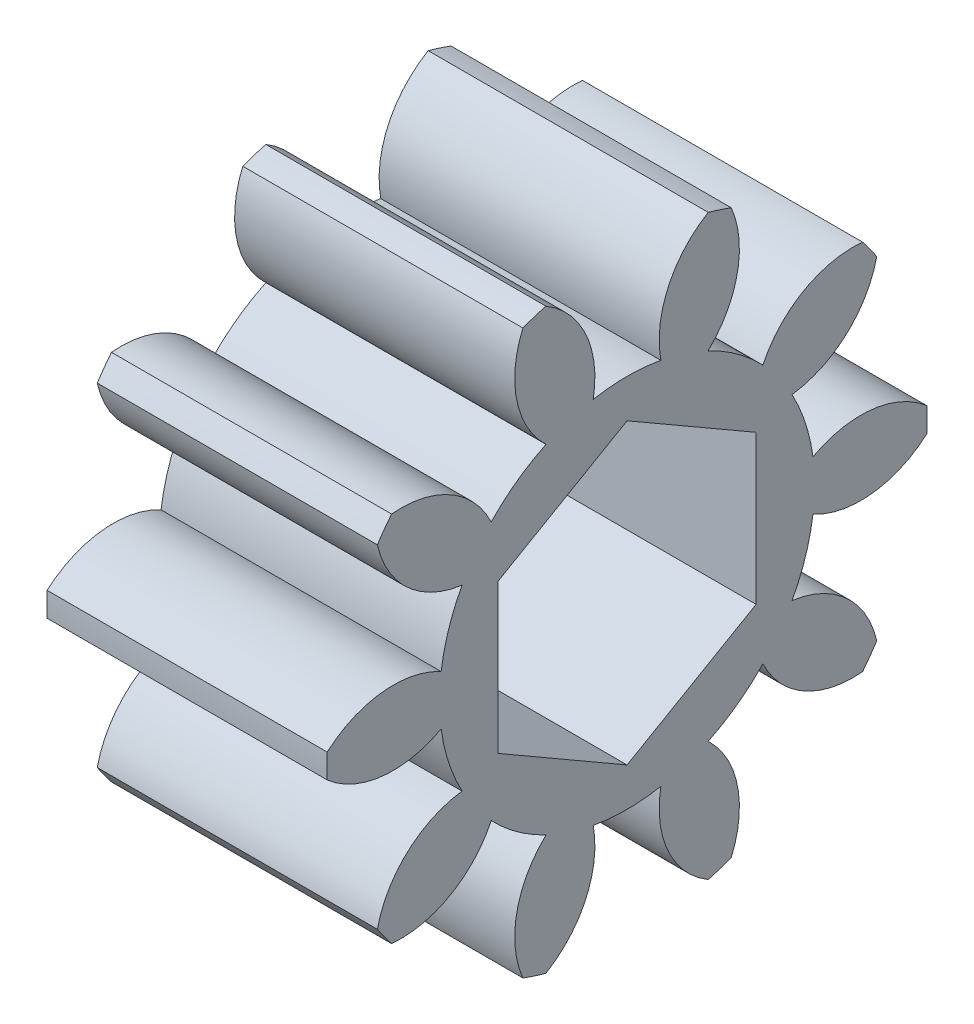
SolidWorks part; units mm, degrees
ref_plane "Plane1" through (0, 0, 0) normal (0, 0, 1) x (1, 0, 0)
ref_plane "Plane2" through (0, 0, 0) normal (0, 1, 0) x (1, 0, 0)
ref_plane "Plane3" through (0, 0, 0) normal (1, 0, 0) x (0, 0, -1)
other "Configuration Table"
sketch "HoldingSke" plane through (0, 0, 0) normal (0, 1, 0) x (1, 0, 0)
  line L0 (0, 0) -> (0.3939, -0.0695)
  line L1 (-15, 0) -> (100, 0) construction
  line L2 (0, 0) -> (-2.1039, 2.3779)
  line L3 (0, 0) -> (-11.863, 4.5341)
  line L4 (0, 0) -> (8.5048, 1.4996)
  line L5 (0, 0) -> (-46.8476, -17.4728)
  line L6 (0, 0) -> (-11.6055, -7.8303)
  line L7 (-2.1039, 2.3779) -> (8.6586, 51.2059)
  line L8 (-76.2, 54.61) -> (-74.4, 54.61)
  line L9 (-67.7845, 28.3722) -> (-49.3413, 33.142)
  line L10 (-76.2, 71.12) -> (104.1128, 71.12)
  line L11 (0, 0) -> (-14, 0)
  line L12 (-76.2, 101.6) -> (-76.113, 101.6)
  line L13 (24.9733, 27.94) -> (52.9518, 28.4284)
  line L14 (24.9733, 27.94) -> (24.9743, 27.94)
  line L15 (24.9733, 27.94) -> (100.4006, 29.5858)
  line L16 (-63.627, -2.5) -> (-12.827, -2.5)
  circle A0 centre (0, 0) radius 5
  circle A1 centre (0, 0) radius 9.374
  circle A2 centre (0, 0) radius 37.5
  circle A3 centre (0, 0) radius 5
  dimension "MHD" = 18.748
  dimension "Hub_dia" = 75
  dimension "Bore" = 10
  dimension "MBD" = 10
  dimension "Num_teeth" = 10
  dimension "Pitch" = 0.4
  dimension "Overall_len" = 50
  dimension "Show_teeth" = 10
  dimension "Thickness" = 14
  dimension "OAL" = 50.0001
  dimension "T_dim" = 1.8
  dimension "Ap" = 14.5
  dimension "H" = 19.05
  dimension "Pitch_radius" = 180.3128
  dimension "Width" = 14
  dimension "Backlash" = 0.087
  dimension "Addendum_fac" = 1
  dimension "Dedendum_fac" = 1.25
  dimension "Clearance_fac" = 0.25
  dimension "Dedendum_add" = 0.001
  dimension "Module" = 2.5
sketch "BasProSke" plane through (0, 0, 0) normal (0, 1, 0) x (1, 0, 0)
  line L0 (-10, 0) -> (60, 0) construction
  line L1 (0, 0) -> (0, 15)
  line L2 (0, 0) -> (14, 0)
  line L3 (14, 0) -> (14, 15)
  line L4 (14, 15) -> (0, 15)
  dimension "Thickness" = 14
  dimension "Diameter" = 30
revolve "Base-Revolve" add sketch "BasProSke" angle 360 about L0
sketch "TooCutSke" plane through (0, 0, 0) normal (1, 0, 0) x (0, 0, -1)
  line L1 (0, 0) -> (0, 107) construction
  line L2 (0, 0) -> (-2.1074, 12.3211) construction
  line L3 (0, 0) -> (-7.6446, 23.5277) construction
  line L4 (-2.1074, 12.3211) -> (-3.8223, 11.7639) construction
  arc A0 (1.6916, 9.2201) -> (-1.6916, 9.2201) centre (0, 0) ccw
  arc A1 (4.0875, 14.4587) -> (-4.0875, 14.4587) centre (0, 0) ccw
  circle A2 centre (0, 0) radius 12.5 construction
  circle A3 centre (0, 0) radius 12.1018 construction
  arc A4 (-1.6916, 9.2201) -> (-4.0875, 14.4587) centre (-6.6064, 10.1395) ccw
  arc A5 (4.0875, 14.4587) -> (1.6916, 9.2201) centre (6.6064, 10.1395) ccw
  dimension "Root_dia" = 18.748
  dimension "Overcut_dia" = 30.0508
  dimension "Pitch_dia" = 25
  dimension "Base_dia" = 24.2037
  dimension "Flank_rad" = 5
  dimension "Half_ang" = 18
  dimension "Half_CT" = 1.8032
extrude "ToothCut" cut sketch "TooCutSke" along normal through all
fillet "Breaks" [suppressed] radius 0.05
fillet "RootFillets" [suppressed] radius 0.626
pattern_circular "TeethCuts" count 10 every 36 about axis through (-10, 0, 0) along (1, 0, 0) of "ToothCut", "RootFillets", "Breaks"
sketch "HubNeaOneSke" plane through (0, 0, 0) normal (-1, 0, 0) x (0, 0, 1)
  circle A0 centre (0, 0) radius 9.374
  dimension "Diameter" = 18.748
extrude "HubNearOne" [suppressed] add sketch "HubNeaOneSke" along normal blind 36.0001
sketch "HubNeaBotSke" plane through (0, 0, 0) normal (-1, 0, 0) x (0, 0, 1)
  circle A0 centre (0, 0) radius 9.374
  dimension "Diameter" = 18.748
extrude "HubNearBoth" [suppressed] add sketch "HubNeaBotSke" along normal blind 18
ref_plane "FarPln" through (14, 0, 0) normal (1, 0, 0) x (0, 0, -1)
sketch "HubFarSke" plane through (14, 0, 0) normal (1, 0, 0) x (0, 0, -1)
  circle A0 centre (0, 0) radius 9.374
  dimension "Diameter" = 18.748
extrude "HubFar" [suppressed] add sketch "HubFarSke" along normal blind 18
sketch "BorSke" plane through (0, 0, 0) normal (1, 0, 0) x (0, 0, -1)
  circle A0 centre (0, 0) radius 5
  dimension "Diameter" = 10
extrude "Bore" cut sketch "BorSke" along normal mid plane 100.0001
sketch "KeySke" plane through (0, 0, 0) normal (1, 0, 0) x (0, 0, -1)
  line L0 (-2, 0) -> (-2, 6.8)
  line L1 (-2, 6.8) -> (2, 6.8)
  line L2 (2, 6.8) -> (2, 0)
  line L3 (0, 0) -> (0, 34) construction
  line L4 (-2, 0) -> (2, 0)
  dimension "Offset" = 6.8
  dimension "Width" = 4
extrude "Keyway" [suppressed] cut sketch "KeySke" along normal mid plane 100.0001
pattern_circular "Keyway2" [suppressed] count 2 every 90 about axis through (-10, 0, 0) along (1, 0, 0)
sketch "Sketch1" plane through (14, 0, 0) normal (1, 0, 0) x (0, 0, -1)
  line L1 (0, -7.4478) -> (6.45, -3.7239)
  line L2 (6.45, -3.7239) -> (6.45, 3.7239)
  line L3 (6.45, 3.7239) -> (0, 7.4478)
  line L4 (0, 7.4478) -> (-6.45, 3.7239)
  line L5 (-6.45, 3.7239) -> (-6.45, -3.7239)
  line L6 (-6.45, -3.7239) -> (0, -7.4478)
  circle A0 centre (0, 0) radius 6.45 construction
extrude "Cut-Extrude1" cut sketch "Sketch1" against normal through all
equation "' \"Module@HoldingSke\" = 6.35"
equation "' \"Num_teeth@HoldingSke\" = 12"
equation "' \"Ap@HoldingSke\" =  20"
equation "' \"Ap@HoldingSke\" = 20"
equation "' \"Width@HoldingSke\" = 0.5 * 25.4"
equation "' \"Hub_dia@HoldingSke\"= 1 * 25.4"
equation "' \"Hub_dia@HoldingSke\" = 1 * 25.4"
equation "' \"Overall_len@HoldingSke\" = 1.0 * 25.4"
equation "' \"Bore@HoldingSke\" = 0.75 * 25.4"
equation "' \"T_dim@HoldingSke\" = 0.1 * 25.4"
equation "' \"Width@KeySke\" = 0.25 * 25.4"
equation "' \"Show_teeth@HoldingSke\" = 13"
equation "' \"Backlash@HoldingSke\" = 0.009 * 25.4"
equation "' \"Addendum_fac@HoldingSke\" = 1.0"
equation "' \"Dedendum_fac@HoldingSke\" = 1.25"
equation "' \"Dedendum_add@HoldingSke\" = 0.00005 * 25.4"
equation "' \"Clearance_fac@HoldingSke\" = 0.25"
equation "\"Pitch@HoldingSke\" = 1 / \"Module@HoldingSke\""
equation "\"Overcut_dia@TooCutSke\" = (\"Num_teeth@HoldingSke\" + 2 * \"Addendum_fac@HoldingSke\") / \"Pitch@HoldingSke\" + 0.002 * 25.4"
equation "\"Pitch_dia@TooCutSke\" = \"Num_teeth@HoldingSke\" / \"Pitch@HoldingSke\""
equation "\"Base_dia@TooCutSke\" = \"Num_teeth@HoldingSke\" / \"Pitch@HoldingSke\" * cos((\"Ap@HoldingSke\"  * 3.14159265 / 180))"
equation "\"Root_dia@TooCutSke\" = (\"Num_teeth@HoldingSke\" + 2) / \"Pitch@HoldingSke\" - 2 * (\"Addendum_fac@HoldingSke\" + \"Dedendum_fac@HoldingSke\") / \"Pitch@HoldingSke\" - \"Dedendum_add@HoldingSke\" * 2"
equation "\"Half_ang@TooCutSke\" = 180 / \"Num_teeth@HoldingSke\""
equation "\"Half_CT@TooCutSke\" = \"Num_teeth@HoldingSke\" / \"Pitch@HoldingSke\" * sin((3.14159265 / 2 / \"Num_teeth@HoldingSke\")) / 2 - 7 * \"Backlash@HoldingSke\" / 4"
equation "\"Flank_rad@TooCutSke\" = \"Num_teeth@HoldingSke\" / \"Pitch@HoldingSke\" / 5"
equation "\"Radius@RootFillets\" = \"Clearance_fac@HoldingSke\" / \"Pitch@HoldingSke\" + \"Dedendum_add@HoldingSke\""
equation "\"Break_rad@Breaks\" = 0.02 / \"Pitch@HoldingSke\""
equation "\"Thickness@HoldingSke\" = \"Width@HoldingSke\""
equation "\"OAL@HoldingSke\" = \"Thickness@HoldingSke\""
equation "\"MHD@HoldingSke\" = (\"Num_teeth@HoldingSke\" + 2) / \"Pitch@HoldingSke\" - 2 * (\"Addendum_fac@HoldingSke\" + \"Dedendum_fac@HoldingSke\")  / \"Pitch@HoldingSke\" - \"Dedendum_add@HoldingSke\" * 2"
equation "\"MBD@HoldingSke\" = (\"Num_teeth@HoldingSke\" + 2) / \"Pitch@HoldingSke\" - 2 * (\"Addendum_fac@HoldingSke\" + \"Dedendum_fac@HoldingSke\")  / \"Pitch@HoldingSke\" - \"Dedendum_add@HoldingSke\" * 2 - 0.002 * 25.4"
equation "\"MHD@HoldingSke\" = ((sgn( \"MHD@HoldingSke\" - \"Hub_dia@HoldingSke\" )-1)*( \"MHD@HoldingSke\" - \"Hub_dia@HoldingSke\" ))/-2+ \"Hub_dia@HoldingSke\""
equation "\"MBD@HoldingSke\" = ((sgn( \"MBD@HoldingSke\" - \"Bore@HoldingSke\" )-1)*( \"MBD@HoldingSke\" - \"Bore@HoldingSke\" ))/-2+ \"Bore@HoldingSke\""
equation "\"OAL@HoldingSke\" = ((sgn( \"OAL@HoldingSke\" - \"Overall_len@HoldingSke\" )+1)*( \"OAL@HoldingSke\" - \"Overall_len@HoldingSke\" ))/2 + \"Overall_len@HoldingSke\" + 0.000002 * 25.4"
equation "\"Num_teeth@TeethCuts\" = int( \"Show_teeth@HoldingSke\" ) + 1"
equation "\"Num_teeth@TeethCuts\" = ((sgn( \"Num_teeth@TeethCuts\" - \"Num_teeth@HoldingSke\" )-1)*( \"Num_teeth@TeethCuts\" - \"Num_teeth@HoldingSke\" ))/-2+ \"Num_teeth@HoldingSke\""
equation "\"Num_teeth@TeethCuts\" = ((sgn( \"Num_teeth@TeethCuts\" - 2.0)+1)*( \"Num_teeth@TeethCuts\" - 2.0))/2 +2.0"
equation "\"Angle@TeethCuts\" = 360.0 / \"Num_teeth@HoldingSke\""
equation "\"Diameter@BasProSke\" = (\"Num_teeth@HoldingSke\" + 2 * \"Addendum_fac@HoldingSke\") / \"Pitch@HoldingSke\""
equation "\"Thickness@BasProSke\"  = \"Thickness@HoldingSke\""
equation "' \"Fillet_rad@BasProSke\" =  \"Thickness@HoldingSke\" * 0.05"
equation "' \"Fillet_rad@BasProSke\" = \"Thickness@HoldingSke\" * 0.05"
equation "\"MHD@HoldingSke\" = ((sgn( \"MHD@HoldingSke\" - \"Root_dia@TooCutSke\" )-1)*( \"MHD@HoldingSke\" - \"Root_dia@TooCutSke\" ))/-2+ \"Root_dia@TooCutSke\""
equation "\"Diameter@HubNeaOneSke\" = \"MHD@HoldingSke\""
equation "\"Length@HubNearOne\" = \"OAL@HoldingSke\" - \"Thickness@BasProSke\""
equation "\"Diameter@HubNeaBotSke\" = \"MHD@HoldingSke\""
equation "\"Length@HubNearBoth\" = ( \"OAL@HoldingSke\" - \"Thickness@BasProSke\" ) / 2.0"
equation "\"Thickness@FarPln\" = \"Thickness@BasProSke\""
equation "\"Diameter@HubFarSke\" = \"MHD@HoldingSke\""
equation "\"Length@HubFar\" = ( \"OAL@HoldingSke\" - \"Thickness@BasProSke\" ) / 2.0"
equation "\"Diameter@BorSke\" = \"MBD@HoldingSke\""
equation "\"D1@Bore\" = \"OAL@HoldingSke\" * 2.0"
equation "\"D1@Keyway\" = \"OAL@HoldingSke\" * 2.0"
equation "\"Offset@KeySke\" = \"T_dim@HoldingSke\" + \"MBD@HoldingSke\" / 2.0"
